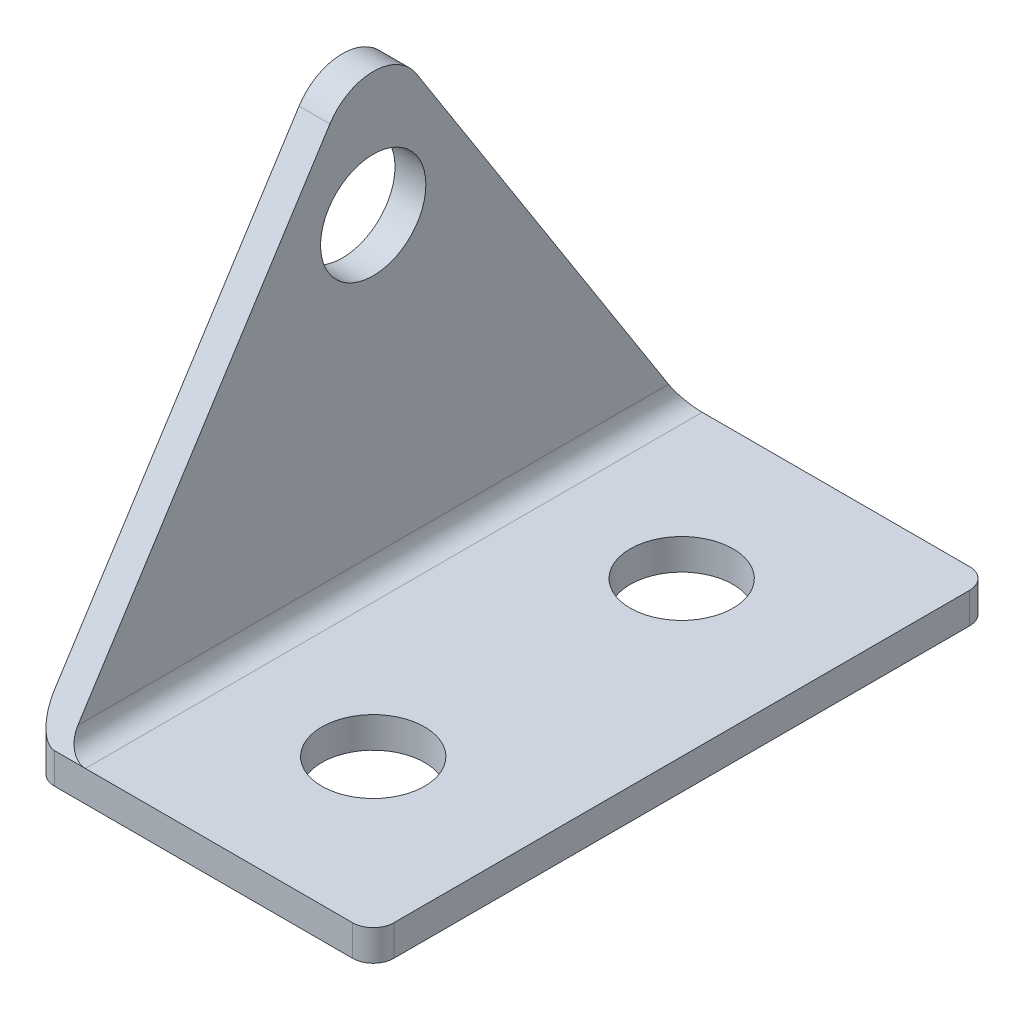
SolidWorks part; units mm, degrees
ref_plane "Front Plane" through (0, 0, 0) normal (0, 0, 1) x (1, 0, 0)
ref_plane "Top Plane" through (0, 0, 0) normal (0, 1, 0) x (1, 0, 0)
ref_plane "Right Plane" through (0, 0, 0) normal (1, 0, 0) x (0, 0, -1)
sketch "Sketch7" plane through (0, 0, 0) normal (0, 0, 1) x (1, 0, 0)
  line L0 (0, 0) -> (0, 63.5)
  line L1 (0, 0) -> (63.5, 0)
  line L3 (63.5, 3.81) -> (3.81, 3.81)
  line L4 (3.81, 3.81) -> (3.81, 63.5)
  line L5 (3.81, 63.5) -> (0, 63.5)
  line L6 (63.5, 3.81) -> (63.5, 0)
extrude "Boss-Extrude1" add sketch "Sketch7" along normal mid plane 76.2
sketch "Sketch8" plane through (3.81, 0, 0) normal (1, 0, 0) x (0, 0, -1)
  line L0 (-38.1, 3.81) -> (0, 63.5)
  line L1 (-38.1, 63.5) -> (38.1, 63.5) construction
  line L2 (0, 63.5) -> (38.1, 3.81)
  line L3 (0, 63.5) -> (38.1, 63.5)
  line L4 (38.1, 63.5) -> (38.1, 3.81)
  line L5 (0, 63.5) -> (-38.1, 63.5)
  line L6 (-38.1, 63.5) -> (-38.1, 3.81)
  line M1 (38.1, 3.81) -> (38.1, 63.5)
  line M2 (38.1, 63.5) -> (-38.1, 63.5)
  line M3 (-38.1, 63.5) -> (-38.1, 3.81)
extrude "Cut-Extrude2" cut sketch "Sketch8" against normal blind 76.2 contours L0 M3 M2 | L2 M2 M1
fillet "Fillet1" radius 6.35 1 edges at (1.905, 63.5, 0)
sketch "Sketch10" plane through (0, 3.81, 0) normal (0, 1, 0) x (1, 0, 0)
  line L0 (3.81, -38.1) -> (41.91, -38.1) construction
  line L1 (63.5, -38.1) -> (3.81, -38.1) construction
  line L2 (41.91, -38.1) -> (41.91, 38.1)
  line L3 (63.5, 38.1) -> (3.81, 38.1) construction
  line L4 (41.91, 38.1) -> (63.5, 38.1)
  line L5 (63.5, 38.1) -> (63.5, -38.1)
  line L6 (63.5, -38.1) -> (41.91, -38.1)
extrude "Cut-Extrude3" cut sketch "Sketch10" against normal blind 76.2
fillet "Fillet2" radius 2.54 4 edges at (0, 1.905, -38.1) (0, 1.905, 38.1) (41.91, 1.905, -38.1) (41.91, 1.905, 38.1)
fillet "Fillet3" radius 2.54 1 edges at (3.81, 3.81, 0)
sketch "Sketch11" plane through (3.81, 0, 0) normal (1, 0, 0) x (0, 0, -1)
  circle A0 centre (0, 42.692) radius 6.5024
extrude "Cut-Extrude4" cut sketch "Sketch11" against normal blind 76.2
sketch "Sketch12" plane through (0, 3.81, 0) normal (0, 1, 0) x (1, 0, 0)
  line L0 (3.81, 0) -> (22.86, 0)
  line L1 (3.81, -36.4787) -> (3.81, 36.4787) construction
  line L2 (22.86, 0) -> (22.86, 19.05)
  line L5 (22.86, 0) -> (22.86, -19.05)
  circle A0 centre (22.86, 19.05) radius 6.35
  circle A1 centre (22.86, -19.05) radius 6.35
extrude "Cut-Extrude5" cut sketch "Sketch12" against normal blind 76.2 contours A1 | A0
